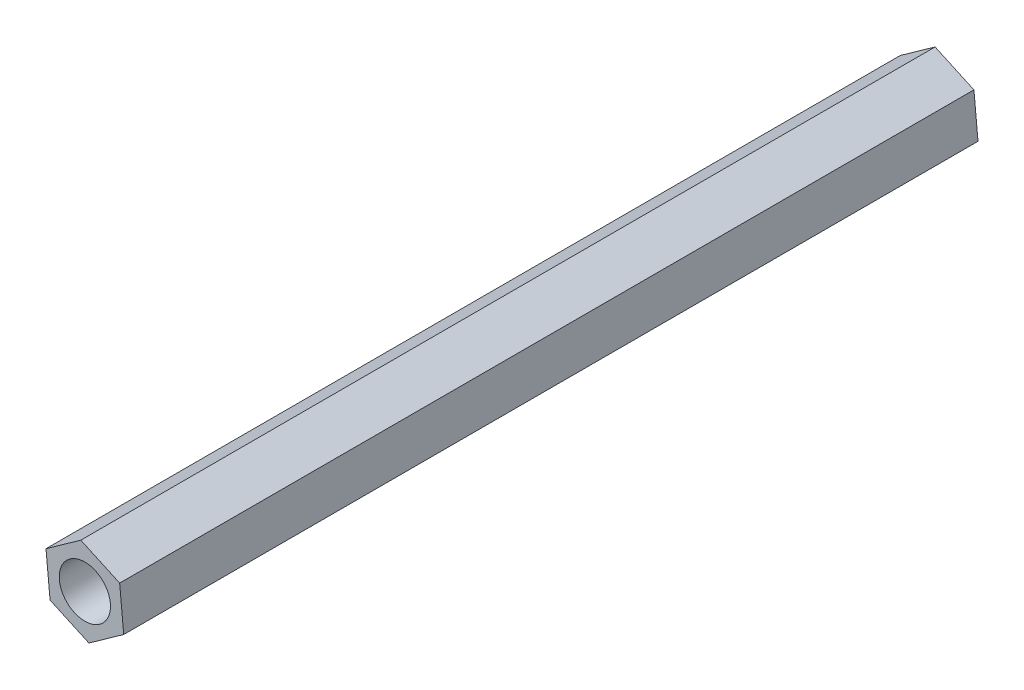
SolidWorks part; units mm, degrees
ref_plane "Front Plane" through (0, 0, 0) normal (0, 0, 1) x (1, 0, 0)
ref_plane "Top Plane" through (0, 0, 0) normal (0, 1, 0) x (1, 0, 0)
ref_plane "Right Plane" through (0, 0, 0) normal (1, 0, 0) x (0, 0, -1)
sketch "Sketch1" plane through (0, 0, 0) normal (0, 0, 1) x (1, 0, 0)
  line L1 (2.0364, 1.4502) -> (-0.2377, 2.4887)
  line L2 (-0.2377, 2.4887) -> (-2.2741, 1.0385)
  line L3 (-2.2741, 1.0385) -> (-2.0364, -1.4502)
  line L4 (-2.0364, -1.4502) -> (0.2377, -2.4887)
  line L5 (0.2377, -2.4887) -> (2.2741, -1.0385)
  line L6 (2.2741, -1.0385) -> (2.0364, 1.4502)
  circle A0 centre (0, 0) radius 1.5
  circle A1 centre (0, 0) radius 2.1651 construction
  dimension "D1" = 3
  dimension "D2" = 2.5
extrude "Boss-Extrude1" add sketch "Sketch1" along normal blind 50
